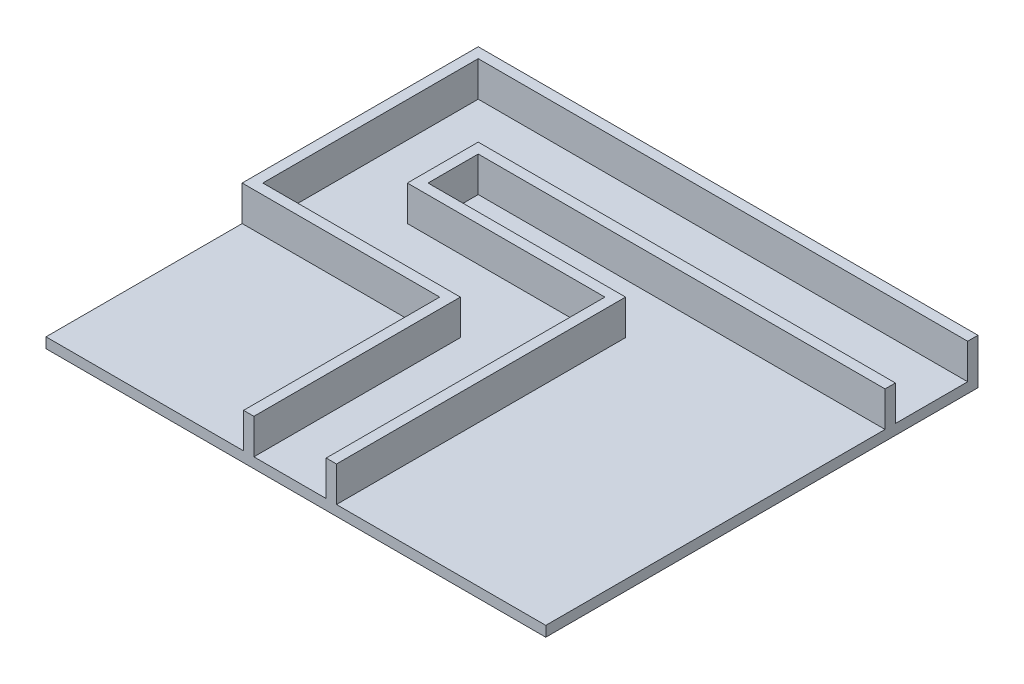
SolidWorks part; units mm, degrees
ref_plane "Front Plane" through (0, 0, 0) normal (0, 0, 1) x (1, 0, 0)
ref_plane "Top Plane" through (0, 0, 0) normal (0, 1, 0) x (1, 0, 0)
ref_plane "Right Plane" through (0, 0, 0) normal (1, 0, 0) x (0, 0, -1)
sketch "Sketch1" plane through (0, 0, 0) normal (0, 1, 0) x (1, 0, 0)
  line L0 (-257.4531, -1067.9012) -> (-257.4531, -67.9012)
  line L1 (-257.4531, -67.9012) -> (-1214.2432, -67.9012)
  line L2 (-1214.2432, -67.9012) -> (-1214.2432, 975.3086)
  line L3 (-1214.2432, 975.3086) -> (1156.1271, 975.3086)
  line L4 (92.5469, -1067.9012) -> (92.5469, 282.0988)
  line L5 (92.5469, 282.0988) -> (-864.2432, 282.0988)
  line L6 (-864.2432, 282.0988) -> (-864.2432, 625.3086)
  line L7 (-864.2432, 625.3086) -> (1156.1271, 625.3086)
  line L8 (142.5469, -1067.9012) -> (142.5469, 332.0988)
  line L9 (142.5469, 332.0988) -> (-814.2432, 332.0988)
  line L10 (-814.2432, 332.0988) -> (-814.2432, 575.3086)
  line L11 (-814.2432, 575.3086) -> (1156.1271, 575.3086)
  line L12 (-307.4531, -1067.9012) -> (-307.4531, -117.9012)
  line L13 (-307.4531, -117.9012) -> (-1264.2432, -117.9012)
  line L14 (-1264.2432, -117.9012) -> (-1264.2432, 1025.3086)
  line L15 (-1264.2432, 1025.3086) -> (1156.1271, 1025.3086)
  line L16 (142.5469, -1067.9012) -> (92.5469, -1067.9012)
  line L17 (-257.4531, -1067.9012) -> (-307.4531, -1067.9012)
  line L18 (1156.1271, 575.3086) -> (1156.1271, 625.3086)
  line L19 (1156.1271, 975.3086) -> (1156.1271, 1025.3086)
  dimension "D1" = 1000
  dimension "D2" = 350
  dimension "D3" = 50
  dimension "D4" = 50
extrude "Boss-Extrude1" add sketch "Sketch1" along normal blind 170
sketch "Sketch2" plane through (0, 0, 0) normal (0, -1, 0) x (1, 0, 0)
  line L1 (-1264.2432, 1067.9012) -> (1156.1271, 1067.9012)
  line L2 (-1264.2432, 1067.9012) -> (-1264.2432, -1025.3086)
  line L3 (-1264.2432, -1025.3086) -> (1156.1271, -1025.3086)
  line L4 (1156.1271, 1067.9012) -> (1156.1271, -1025.3086)
  point P5 (-1324.5749, 1054.4155)
  point P7 (0, 0)
  point P8 (0, 0)
extrude "Boss-Extrude2" add sketch "Sketch2" along normal blind 50
